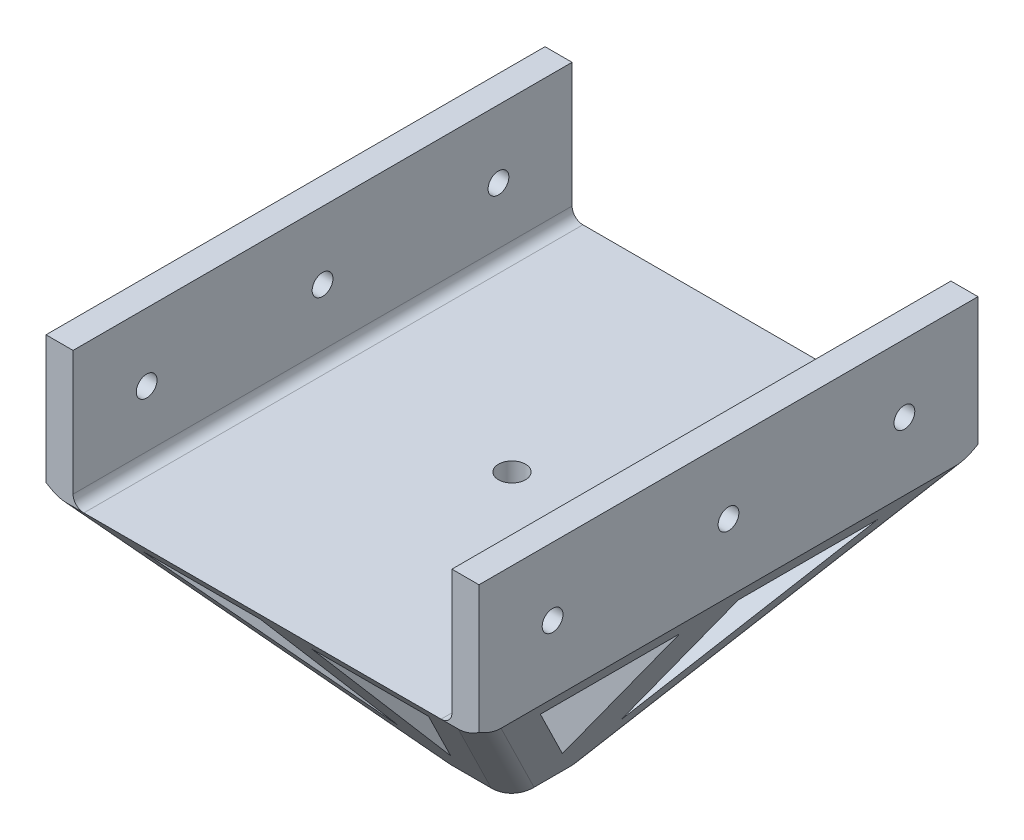
SolidWorks part; units mm, degrees
ref_plane "Front Plane" through (0, 0, 0) normal (0, 0, 1) x (1, 0, 0)
ref_plane "Top Plane" through (0, 0, 0) normal (0, 1, 0) x (1, 0, 0)
ref_plane "Right Plane" through (0, 0, 0) normal (1, 0, 0) x (0, 0, -1)
sketch "Sketch2" plane through (0, 0, 0) normal (0, 0, 1) x (1, 0, 0)
  line L0 (95.25, 31.75) -> (101.6, 31.75)
  line L2 (0, 0) -> (0, 31.75)
  line L3 (0, 31.75) -> (6.35, 31.75)
  line L4 (101.6, 0) -> (101.6, 31.75)
  line L6 (6.35, 31.75) -> (6.35, 2.54)
  line L7 (8.89, 0) -> (92.71, 0)
  line L8 (95.25, 31.75) -> (95.25, 2.54)
  line L9 (101.6, 0) -> (60.325, -57.15)
  line L10 (60.325, -57.15) -> (41.275, -57.15)
  line L11 (41.275, -57.15) -> (0, 0)
  arc A0 (6.35, 2.54) -> (8.89, 0) centre (8.89, 2.54) ccw
  arc A1 (92.71, 0) -> (95.25, 2.54) centre (92.71, 2.54) ccw
  point P17 (0, 0)
  point P27 (50.8, 0)
  point P28 (50.8, -57.15)
  dimension "D6" = 2.54
  dimension "D1" = 19.05
  dimension "D2" = 31.75
  dimension "D3" = 57.15
  dimension "D4" = 6.35
  dimension "D5" = 88.9
extrude "Boss-Extrude1" add sketch "Sketch2" along normal blind 117.094
sketch "Sketch3" plane through (101.6, 0, 0) normal (1, 0, 0) x (0, 0, -1)
  line L0 (-99.822, 15.875) -> (-58.547, 15.875) construction
  line L1 (-58.547, 15.875) -> (-17.272, 15.875) construction
  line L3 (0, 0) -> (-117.094, 0) construction
  line L5 (-117.094, 0) -> (-117.094, 31.75) construction
  circle A0 centre (-99.822, 15.875) radius 2.4384
  circle A1 centre (-58.547, 15.875) radius 2.4384
  circle A2 centre (-17.272, 15.875) radius 2.4384
  point P9 (-58.547, 0)
  dimension "D1" = 4.8768
  dimension "D2" = 15.875
  dimension "D3" = 41.275
extrude "Cut-Extrude1" cut sketch "Sketch3" against normal through all
sketch "Sketch4" plane through (0, 0, 0) normal (0, 1, 0) x (1, 0, 0)
  line L0 (92.71, 0) -> (8.89, 0) construction
  line L1 (8.89, -117.094) -> (8.89, 0) construction
  circle A0 centre (50.8, -58.547) radius 3.175
  point P2 (50.8, 0)
  point P3 (8.89, -58.547)
  dimension "D1" = 6.35
extrude "Cut-Extrude2" cut sketch "Sketch4" against normal through all
sketch "Sketch5" plane through (101.6, 0, 0) normal (1, 0, 0) x (0, 0, -1)
  line L0 (-117.094, 0) -> (-68.072, -57.15)
  line L1 (-68.072, -57.15) -> (-49.022, -57.15)
  line L2 (-49.022, -57.15) -> (0, 0)
  line L3 (-117.094, 0) -> (0, 0) construction
  line L4 (-117.094, -57.15) -> (0, -57.15) construction
  line L5 (-117.094, 0) -> (-117.094, -57.15)
  line L6 (-117.094, -57.15) -> (-68.072, -57.15)
  line L7 (-49.022, -57.15) -> (0, -57.15)
  line L8 (0, -57.15) -> (0, 0)
  point P11 (-58.547, -57.15)
  dimension "D3" = 19.05
extrude "Cut-Extrude3" cut sketch "Sketch5" against normal through all contours L5 L6 L0 | L7 L8 L2
fillet "Fillet1" radius 6.35 4 edges at (80.9625, -28.575, 24.511) (80.9625, -28.575, 92.583) (20.6375, -28.575, 24.511) (20.6375, -28.575, 92.583)
sketch "Sketch7" plane through (101.6, 0, 0) normal (1, 0, 0) x (0, 0, -1)
  line L6 (-65.4227, -44.45) -> (-65.4227, -6.35)
  line L7 (-51.6713, -44.45) -> (-51.6713, -6.35)
  line L9 (-58.547, -52.4658) -> (-18.9899, -6.35)
  line L10 (-18.9899, -6.35) -> (-98.1041, -6.35)
  line L11 (-98.1041, -6.35) -> (-58.547, -52.4658)
  line L12 (-58.547, -52.4658) -> (-18.9899, -6.35)
  line L13 (-18.9899, -6.35) -> (-98.1041, -6.35)
  line L14 (-98.1041, -6.35) -> (-58.547, -52.4658)
  point P4 (-46.4627, -38.3779)
  dimension "D2" = 38.1
  dimension "D1" = 6.35
extrude "Cut-Extrude4" cut sketch "Sketch7" against normal through all contours L13 L14 L6 | L12 L13 L7
sketch "Sketch8" plane through (0, 0, 117.094) normal (0, 0, 1) x (1, 0, 0)
  line L21 (44.7828, -44.45) -> (44.7828, -6.35)
  line L22 (56.8172, -44.45) -> (56.8172, -6.35)
  line L26 (50.8, -52.7815) -> (84.3339, -6.35)
  line L27 (17.2661, -6.35) -> (50.8, -52.7815)
  line L28 (84.3339, -6.35) -> (17.2661, -6.35)
  line L29 (50.8, -52.7815) -> (84.3339, -6.35)
  line L30 (17.2661, -6.35) -> (50.8, -52.7815)
  line L31 (84.3339, -6.35) -> (17.2661, -6.35)
  dimension "D2" = 38.1
  dimension "D1" = 6.35
extrude "Cut-Extrude5" cut sketch "Sketch8" against normal blind 110.744 contours L21 L31 L30 | L29 L31 L22
